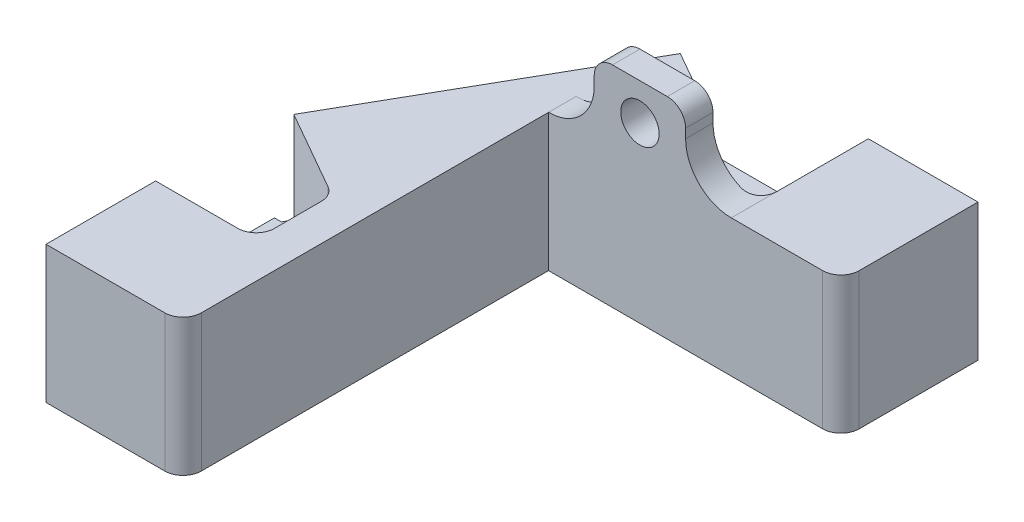
SolidWorks part; units mm, degrees
ref_plane "Plan de face" through (0, 0, 0) normal (0, 0, 1) x (1, 0, 0)
ref_plane "Plan de dessus" through (0, 0, 0) normal (0, 1, 0) x (1, 0, 0)
ref_plane "Plan de droite" through (0, 0, 0) normal (1, 0, 0) x (0, 0, -1)
sketch "Esquisse2" plane through (0, 0, 0) normal (0, 1, 0) x (1, 0, 0)
  line L0 (0, 0) -> (0, -20) construction
  line L1 (0, 0) -> (20, 0) construction
  line L3 (74.8306, 20) -> (0, 20) construction
  line L4 (0, 20) -> (-20, -15) construction
  line L5 (-20, -15) -> (-20, -54.5729) construction
  line L10 (20, 0) -> (0, 0)
  line L11 (0, 0) -> (0, -20)
  line L14 (0, 80.5652) -> (0, -55.5551) construction
  line L15 (-32.2772, -15) -> (18.2274, -15) construction
  line L17 (0, 15) -> (32, 15)
  line L18 (-14.2412, -15) -> (-15, -15)
  line L19 (-15, -15) -> (-15, -40)
  line L20 (0, 15) -> (2.1313, 13.652)
  line L21 (2.1313, 13.652) -> (-14.2412, -15)
  line L22 (2.1313, 13.652) -> (-2.2099, 16.1327) construction
  line L23 (0, 15) -> (0, 20) construction
  line L24 (0, -20) -> (0, -40)
  line L26 (20, 0) -> (32, 0)
  line L27 (32, 0) -> (32, 15)
  line L28 (0, -40) -> (-15, -40)
  dimension "D1" = 20
  dimension "D2" = 5
  dimension "D3" = 20
  dimension "D4" = 20
  dimension "D5" = 5
  dimension "D6" = 5
  dimension "D7" = 5
  dimension "D8" = 33
  dimension "D9" = 32.311
  dimension "D11" = 20
  dimension "D12" = 12
extrude "Boss.-Extru.1" add sketch "Esquisse2" along normal blind 5 contours L28 L24 L11 L10 L26 L27 L17 L20 L21 L19
sketch "Esquisse3" plane through (0, 5, 0) normal (0, 1, 0) x (1, 0, 0)
  line L0 (1.6352, 12.7838) -> (11.1859, 7.3263) construction
  line L1 (11.1859, 7.3263) -> (5.2322, -3.0927) construction
  line L2 (5.2322, -3.0927) -> (-4.3185, 2.3649) construction
  line L3 (-7.7914, -3.7128) -> (1.7592, -9.1704) construction
  line L4 (1.7592, -9.1704) -> (-4.1944, -19.5893) construction
  line L5 (-4.1944, -19.5893) -> (-13.7451, -14.1318) construction
  line L6 (20, 15) -> (20, 4) construction
  line L7 (20, 4) -> (32, 4) construction
  line L8 (32, 4) -> (32, 15) construction
  line L15 (2.1313, 13.652) -> (-14.2412, -15) construction
  line L17 (-15, -15) -> (-15, -40) construction
  line L27 (-15, -28) -> (-4, -28) construction
  line L28 (-4, -28) -> (-4, -40) construction
  line L29 (-4, -40) -> (-15, -40) construction
  line L30 (20, 15) -> (20, 4)
  line L31 (20, 4) -> (32, 4)
  line L32 (1.6352, 12.7838) -> (11.1859, 7.3263)
  line L33 (11.1859, 7.3263) -> (5.2322, -3.0927)
  line L34 (5.2322, -3.0927) -> (-4.3185, 2.3649)
  line L35 (9.6672, 3) -> (32, 3) construction
  line L36 (-7.7914, -3.7128) -> (1.7592, -9.1704)
  line L37 (1.7592, -9.1704) -> (-4.1944, -19.5893)
  line L38 (-4.1944, -19.5893) -> (-13.7451, -14.1318)
  line L41 (-15, -28) -> (-4, -28)
  line L42 (-4, -28) -> (-4, -40)
  line L43 (-3.0161, 1.6207) -> (-6.4891, -4.457)
  line L44 (-0.4114, 0.1322) -> (-3.8843, -5.9455)
  line L45 (8.7137, 3) -> (18.7137, 3)
  line L46 (18.7137, 3) -> (18.7137, 0)
  line L47 (8.7137, 3) -> (8.7137, 10.0343) construction
  line L48 (8.7137, 3) -> (8.7137, 8.7389)
  line L49 (26, 4) -> (26, 15) construction
  line L50 (-4, -34) -> (-15, -34) construction
  line L51 (20, 0) -> (20, -20) construction
  line L52 (-1.2176, -14.3798) -> (-10.7683, -8.9223) construction
  line L53 (8.209, 2.1168) -> (-1.3416, 7.5743) construction
  line L54 (20, -20) -> (0, -20) construction
  line L55 (20, -10) -> (0, -10) construction
  line L56 (10, -20) -> (10, 0) construction
  line L57 (0, -40) -> (-15, -40) construction
  line L58 (0, 15) -> (32, 15) construction
  line L59 (32, 0) -> (32, 15) construction
  line L60 (32, 0) -> (0, 0) construction
  line L61 (20, 15) -> (20, 0) construction
  line L62 (18.7137, 3) -> (20, 3)
  line L63 (-15, -40) -> (0, -40)
  line L64 (0, -40) -> (0, 0)
  line L65 (0, 0) -> (32, 0)
  line L66 (32, 0) -> (32, 15)
  line L67 (32, 15) -> (0, 15)
  line L68 (0, 15) -> (2.1313, 13.652)
  line L69 (2.1313, 13.652) -> (-14.2412, -15)
  line L70 (-15, -15) -> (-15, -40)
  line L71 (-15, -40) -> (0, -40)
  line L72 (0, -40) -> (0, 0)
  line L73 (0, 0) -> (32, 0)
  line L74 (32, 0) -> (32, 15)
  line L75 (32, 15) -> (0, 15)
  line L76 (0, 15) -> (2.1313, 13.652)
  line L77 (2.1313, 13.652) -> (-14.2412, -15)
  line L78 (-15, -15) -> (-15, -40)
  line L79 (20, 3) -> (20, 4)
  line L80 (-4, -28) -> (0, -28)
  line L81 (-4.1944, -19.5893) -> (0, -21.9861)
  line L82 (-4, -40) -> (-4, -19.7004) construction
  line L83 (-4, -28) -> (-4, -19.7004)
  line L84 (-6.055, -0.674) -> (-19.48, 6.9975) construction
  line L85 (-2.7308, 5.1432) -> (5.1702, 0.6284) construction
  line L86 (-3.227, 4.275) -> (4.6741, -0.2399) construction
  line L94 (-14.2412, -15) -> (-15, -15)
  line L95 (-14.2412, -15) -> (-15, -15)
  circle A0 centre (13.0159, 12) radius 4 construction
  circle A1 centre (-10, -23.3034) radius 4 construction
  dimension "D8" = 8
  dimension "D9" = 20
  dimension "D2" = 11
  dimension "D3" = 12
  dimension "D4" = 0
  dimension "D5" = 24
  dimension "D6" = 1.5
  dimension "D7" = 19
  dimension "D10" = 20
  dimension "D11" = 3
  dimension "D12" = 10
  dimension "D13" = 3
  dimension "D14" = 10
  dimension "D15" = 9.1
  dimension "D16" = 2.8
  dimension "D17" = 1
  dimension "D18" = 9.1
  dimension "D20" = 20
extrude "Boss.-Extru.2" add sketch "Esquisse3" along normal blind 10
sketch "Esquisse4" plane through (-4.2742, 0, -2.4424) normal (-0.8682, 0, -0.4961) x (-0.4961, 0, 0.8682)
  line L0 (-12.9107, 5) -> (-12.9107, 0) construction
  line L1 (-12.9107, 10) -> (19.0893, 10) construction
  line L2 (3.5893, 15) -> (3.5893, 0) construction
  line L3 (-11.9107, 15) -> (19.0893, 15) construction
  line L8 (20.0893, 5) -> (19.0893, 5)
  line L9 (20.0893, 5) -> (19.0893, 5)
  line L10 (19.0893, 5) -> (19.0893, 15)
  line L19 (19.0893, 5) -> (19.0893, 15)
  line L23 (-12.9107, 5) -> (-12.9107, 0)
  line L35 (-12.9107, 5) -> (-12.9107, 0)
  line L49 (-12.9107, 0) -> (20.0893, 0)
  line L55 (-12.9107, 0) -> (20.0893, 0)
  line L56 (20.0893, 0) -> (20.0893, 5)
  line L58 (19.0893, 15) -> (-11.9107, 15)
  line L59 (19.0893, 15) -> (-11.9107, 15)
  line L64 (-11.9107, 15) -> (-11.9107, 5)
  line L65 (-11.9107, 15) -> (-11.9107, 5)
  line L66 (-11.9107, 5) -> (-12.9107, 5)
  line L67 (-11.9107, 5) -> (-12.9107, 5)
  line L68 (20.0893, 0) -> (20.0893, 5)
  circle A0 centre (-6.4107, 10) radius 2.8
  circle A1 centre (13.5893, 10) radius 2.8
  dimension "D2" = 5.6
  dimension "D3" = 20
  dimension "D4" = 10
  dimension "D5" = 6.5
  dimension "D1" = 0
extrude "Enlèv. mat.-Extru.1" cut sketch "Esquisse4" against normal blind 9.1 contours A0 | A1
sketch "Esquisse5" plane through (-15, 0, 0) normal (-1, 0, 0) x (0, 0, 1)
  line L0 (28, 10) -> (40, 10) construction
  line L1 (34, 15) -> (34, 0) construction
  line L6 (28, 15) -> (28, 5)
  line L7 (40, 0) -> (40, 15)
  line L13 (40, 0) -> (40, 15)
  line L24 (28, 5) -> (15, 5)
  line L28 (28, 5) -> (15, 5)
  line L31 (15, 5) -> (15, 0)
  line L35 (15, 0) -> (40, 0)
  line L36 (15, 0) -> (40, 0)
  line L37 (15, 5) -> (15, 0)
  line L38 (28, 15) -> (28, 5)
  line L39 (40, 15) -> (28, 15)
  line L40 (40, 15) -> (28, 15)
  circle A0 centre (34, 10) radius 2.8
  dimension "D2" = 5.6
  dimension "D1" = 0
extrude "Enlèv. mat.-Extru.2" cut sketch "Esquisse5" against normal blind 9.1 contours A0
sketch "Esquisse6" plane through (0, 0, -15) normal (0, 0, -1) x (-1, 0, 0)
  line L0 (-20, 0) -> (-32, 0) construction
  line L1 (-26, 15) -> (-26, 0) construction
  line L2 (0, 0) -> (-32, 0) construction
  line L3 (-20, 10) -> (-32, 10) construction
  line L6 (0, 5) -> (-20, 5)
  line L7 (0, 0) -> (0, 5)
  line L11 (-32, 15) -> (-32, 0)
  line L13 (0, 0) -> (0, 5)
  line L17 (-32, 15) -> (-32, 0)
  line L28 (-32, 0) -> (0, 0)
  line L30 (-32, 0) -> (0, 0)
  line L32 (0, 5) -> (-20, 5)
  line L33 (-20, 5) -> (-20, 15)
  line L34 (-20, 5) -> (-20, 15)
  line L35 (-20, 15) -> (-32, 15)
  line L37 (-20, 15) -> (-32, 15)
  circle A0 centre (-26, 10) radius 2.8
  dimension "D2" = 5.6
  dimension "D1" = 0
extrude "Enlèv. mat.-Extru.3" cut sketch "Esquisse6" against normal blind 9.1 contours A0
sketch "Esquisse10" plane through (0, 15, 0) normal (0, 1, 0) x (1, 0, 0)
  line L0 (8.7137, 3) -> (0, 3)
  line L1 (0, 0) -> (0, 3)
  line L2 (20, 3) -> (20, 0)
  line L3 (10, 0) -> (10, -13.8265) construction
  line L4 (5, 3) -> (5, 0)
  line L6 (15, 0) -> (15, 3)
  line L14 (-15, -40) -> (0, -40)
  line L15 (0, -40) -> (0, 0)
  line L16 (0, 0) -> (32, 0)
  line L17 (32, 0) -> (32, 15)
  line L18 (32, 15) -> (20, 15)
  line L19 (20, 15) -> (20, 3)
  line L20 (20, 3) -> (8.7137, 3)
  line L21 (8.7137, 3) -> (8.7137, 8.7389)
  line L22 (8.7137, 8.7389) -> (1.6352, 12.7838)
  line L23 (1.6352, 12.7838) -> (-13.7451, -14.1318)
  line L24 (-13.7451, -14.1318) -> (-4, -19.7004)
  line L25 (-4, -19.7004) -> (-4, -28)
  line L26 (-4, -28) -> (-15, -28)
  line L27 (-15, -28) -> (-15, -40)
  line L28 (-15, -40) -> (0, -40)
  line L29 (0, -40) -> (0, 0)
  line L30 (0, 0) -> (32, 0)
  line L31 (32, 0) -> (32, 15)
  line L32 (32, 15) -> (20, 15)
  line L33 (20, 15) -> (20, 3)
  line L34 (20, 3) -> (8.7137, 3)
  line L35 (8.7137, 3) -> (8.7137, 8.7389)
  line L36 (8.7137, 8.7389) -> (1.6352, 12.7838)
  line L37 (1.6352, 12.7838) -> (-13.7451, -14.1318)
  line L38 (-13.7451, -14.1318) -> (-4, -19.7004)
  line L39 (-4, -19.7004) -> (-4, -28)
  line L40 (-4, -28) -> (-15, -28)
  line L41 (-15, -28) -> (-15, -40)
  line M17 (0, 0) -> (32, 0)
  line M21 (20, 3) -> (8.7137, 3)
  dimension "D2" = 10
  dimension "D3" = 10
  dimension "D1" = 0
extrude "Boss.-Extru.3" add sketch "Esquisse10" along normal blind 8 contours L2 L0 L1 M21 M17
sketch "Esquisse8" plane through (0, 0, 0) normal (0, 0, 1) x (1, 0, 0)
  line L0 (20, 19) -> (0, 19) construction
  line L1 (10, 15) -> (10, 0) construction
  line L6 (5, 15) -> (0, 15)
  line L9 (32, 0) -> (32, 15)
  line L11 (5, 15) -> (0, 15)
  line L15 (0, 15) -> (0, 0)
  line L23 (0, 15) -> (0, 0)
  line L26 (32, 0) -> (32, 15)
  line L30 (0, 0) -> (32, 0)
  line L31 (0, 0) -> (32, 0)
  line L43 (15, 23) -> (5, 23)
  line L45 (15, 23) -> (5, 23)
  line L46 (32, 15) -> (15, 15)
  line L47 (32, 15) -> (15, 15)
  line L48 (15, 15) -> (15, 23)
  line L49 (15, 15) -> (15, 23)
  line L50 (5, 23) -> (5, 15)
  line L51 (5, 23) -> (5, 15)
  circle A0 centre (10, 19) radius 2.1
  dimension "D2" = 10
  dimension "D3" = 4.2
  dimension "D4" = 19
  dimension "D1" = 0
extrude "Enlèv. mat.-Extru.5" cut sketch "Esquisse8" against normal blind 9.1 contours A0
sketch "Esquisse9" plane through (0, 5, 0) normal (0, 1, 0) x (1, 0, 0)
  line L0 (0, -40) -> (0, 0) construction
  line L1 (0, 0) -> (5, 0) construction
  line L2 (0, -20) -> (20, -20) construction
  line L3 (0, -40) -> (0, 0) construction
  line L4 (20, -20) -> (20, 0) construction
  line L5 (-15, -28) -> (-4, -28)
  line L6 (-4, -28) -> (-4, -19.7004)
  line L7 (-4, -19.7004) -> (-13.7451, -14.1318)
  line L8 (-13.7451, -14.1318) -> (-14.2412, -15)
  line L9 (-15, -15) -> (-15, -28)
  line L10 (-15, -28) -> (-4, -28)
  line L11 (-4, -28) -> (-4, -19.7004)
  line L12 (-4, -19.7004) -> (-13.7451, -14.1318)
  line L13 (-13.7451, -14.1318) -> (-14.2412, -15)
  line L14 (-15, -15) -> (-15, -28)
  line L15 (5, 0) -> (15, 0) construction
  line L16 (10, -20) -> (10, 0) construction
  line L17 (8.7137, 3) -> (20, 3)
  line L18 (20, 3) -> (20, 15)
  line L19 (20, 15) -> (0, 15)
  line L20 (0, 15) -> (2.1313, 13.652)
  line L21 (2.1313, 13.652) -> (1.6352, 12.7838)
  line L22 (1.6352, 12.7838) -> (8.7137, 8.7389)
  line L23 (8.7137, 8.7389) -> (8.7137, 3)
  line L24 (8.7137, 3) -> (20, 3)
  line L25 (20, 3) -> (20, 15)
  line L26 (20, 15) -> (0, 15)
  line L27 (0, 15) -> (2.1313, 13.652)
  line L28 (2.1313, 13.652) -> (1.6352, 12.7838)
  line L29 (1.6352, 12.7838) -> (8.7137, 8.7389)
  line L30 (8.7137, 8.7389) -> (8.7137, 3)
  line L31 (20, -10) -> (0, -10) construction
  line L32 (-14.2412, -15) -> (-15, -15)
  line L33 (-14.2412, -15) -> (-15, -15)
  circle A0 centre (-10, -22) radius 2.1
  circle A1 centre (14, 10) radius 2.1
  point P30 (10, -3.251)
  point P31 (10, 0)
  dimension "D3" = 4.2
  dimension "D4" = 5
  dimension "D5" = 5
  dimension "D6" = 14
  dimension "D7" = 22
  dimension "D8" = 20
  dimension "D9" = 12
  dimension "D10" = 20
  dimension "D11" = 20
  dimension "D12" = 4
  dimension "D1" = 0
  dimension "D2" = 0
extrude "Enlèv. mat.-Extru.6" cut sketch "Esquisse9" against normal blind 14 contours A0 | A1
fillet "Congé2" radius 5 2 edges at (15, 15, -1.5) (5, 15, -1.5)
fillet "Congé1" radius 2 8 edges at (32, 7.5, 0) (0, 7.5, 40) (8.7137, 10, -8.7389) (20, 10, -3) (-4, 10, 28) (-4, 10, 19.7004) (15, 23, -1.5) (5, 23, -1.5)
